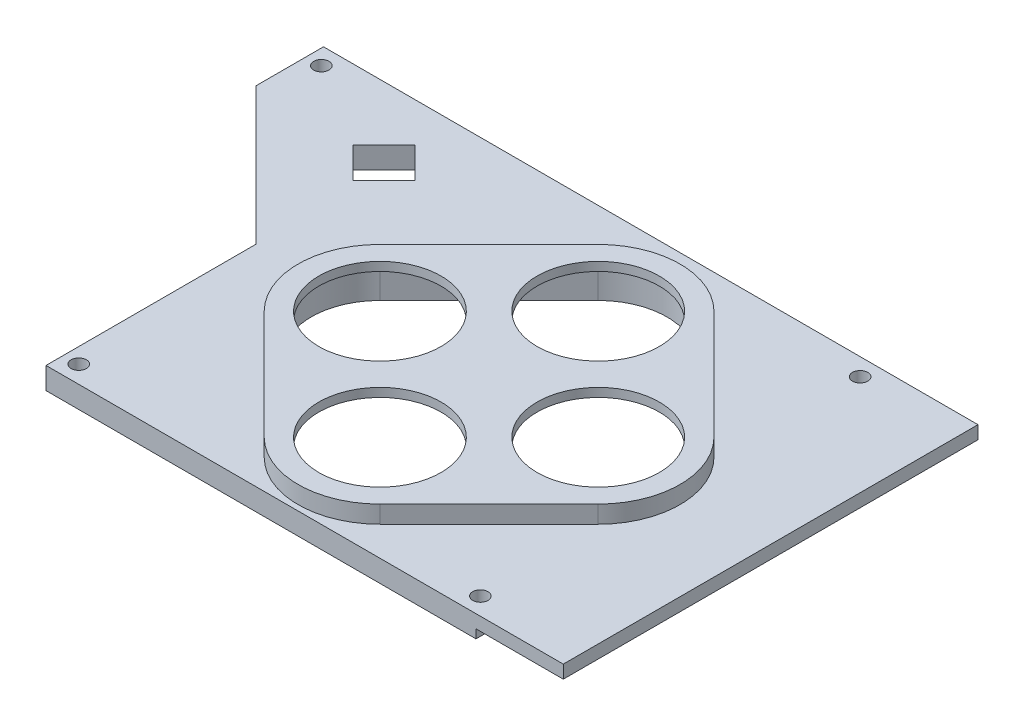
SolidWorks part; units mm, degrees
ref_plane "Front Plane" through (0, 0, 0) normal (0, 0, 1) x (1, 0, 0)
ref_plane "Top Plane" through (0, 0, 0) normal (0, 1, 0) x (1, 0, 0)
ref_plane "Right Plane" through (0, 0, 0) normal (1, 0, 0) x (0, 0, -1)
sketch "Sketch1" plane through (0, 0, 0) normal (0, 1, 0) x (1, 0, 0)
  line L1 (-100, 47.5) -> (100, 47.5)
  line L2 (-100, 47.5) -> (-100, -47.5)
  line L3 (-100, -47.5) -> (100, -47.5)
  line L4 (100, 47.5) -> (100, -47.5)
  line L5 (-100, 47.5) -> (100, -47.5) construction
  line L6 (-100, -47.5) -> (100, 47.5) construction
  circle A0 centre (-96, 43.5) radius 1.75
  circle A1 centre (-96, -43.5) radius 1.75
  circle A2 centre (97, 43.5) radius 1.75
  circle A3 centre (97, -43.5) radius 1.75
  point P0 (0, 0)
  dimension "D4" = 3.5
  dimension "D1" = 200
  dimension "D2" = 95
  dimension "D3" = 4
  dimension "D5" = 4
  dimension "D6" = 4
  dimension "D7" = 4
  dimension "D8" = 3
  dimension "D9" = 4
  dimension "D10" = 4
  dimension "D11" = 3
extrude "Boss-Extrude1" add sketch "Sketch1" along normal blind 5
sketch "Sketch2" plane through (0, 5, 0) normal (0, 1, 0) x (1, 0, 0)
  line L0 (-100, 47.5) -> (-100, -47.5) construction
  line L1 (-100, -47.5) -> (100, -47.5) construction
  line L3 (100, -47.5) -> (100, 47.5) construction
  line L4 (58, 22.5) -> (58, -27.5) construction
  line L5 (33, -2.5) -> (83, -2.5) construction
  line L6 (21.8631, -13.6369) -> (46.8631, -38.6369)
  line L7 (69.1369, -38.6369) -> (94.1369, -13.6369)
  line L8 (46.8631, 33.6369) -> (21.8631, 8.6369)
  line L9 (69.1369, 33.6369) -> (94.1369, 8.6369)
  circle A0 centre (-82, -27.5) radius 12.5
  circle A1 centre (58, 22.5) radius 15.75
  circle A2 centre (58, -27.5) radius 15.75
  circle A3 centre (83, -2.5) radius 15.75
  circle A4 centre (33, -2.5) radius 15.75
  point P13 (58, -2.5)
  point P17 (58, -2.5)
  dimension "D3" = 25
  dimension "D4" = 31.5
  dimension "D1" = 18
  dimension "D2" = 20
  dimension "D5" = 42
  dimension "D6" = 20
  dimension "D7" = 50
extrude "Cut-Extrude1" cut sketch "Sketch2" against normal up to surface (5 mm away) contours A4 | A4 L6 A2 L7 A3 L9 A1 L8 | A2 | A3 | A1 | A0 up to face at (0, 0, 0)
sketch "Sketch4" plane through (0, 0, 0) normal (0, -1, 0) x (1, 0, 0)
  line L0 (-100, -47.5) -> (-100, 47.5) construction
  line L1 (-93.5, 41) -> (-71.5, 41)
  line L2 (-93.5, 41) -> (-93.5, -41)
  line L3 (-93.5, -41) -> (-71.5, -41)
  line L4 (-71.5, 41) -> (-71.5, -41)
  line L5 (-93.5, 41) -> (-71.5, -41) construction
  line L6 (-93.5, -41) -> (-71.5, 41) construction
  line L7 (-100, 0) -> (-82.5, 0) construction
  line L8 (-82.5, 0) -> (-82.5, -19.5) construction
  line L9 (-90.5, -1) -> (-74.5, -1)
  line L10 (-90.5, -1) -> (-90.5, -38)
  line L11 (-90.5, -38) -> (-74.5, -38)
  line L12 (-74.5, -1) -> (-74.5, -38)
  line L13 (-90.5, -1) -> (-74.5, -38) construction
  line L14 (-90.5, -38) -> (-74.5, -1) construction
  point P0 (-82.5, 0)
  point P11 (-82.5, -19.5)
  circle M17 centre (-82, 27.5) radius 12.5
  dimension "D1" = 22
  dimension "D2" = 6.5
  dimension "D3" = 82
  dimension "D4" = 3
  dimension "D5" = 3
  dimension "D6" = 40
extrude "Boss-Extrude2" add sketch "Sketch4" along normal blind 4.2 contours L4 L2 L3 L9 L12 L11 L10 M17
sketch "Sketch5" plane through (0, 5, 0) normal (0, 1, 0) x (1, 0, 0)
  circle A0 centre (-82, -27.5) radius 17
  dimension "D1" = 34
sketch "Sketch6" plane through (0, 5, 0) normal (0, 1, 0) x (1, 0, 0)
  line L0 (-100, -47.5) -> (100, -47.5) construction
  line L1 (-100, 47.5) -> (-120, 47.5)
  line L2 (-100, 47.5) -> (-100, -47.5)
  line L3 (-100, -47.5) -> (-120, -47.5)
  line L4 (-120, 47.5) -> (-120, -47.5)
  line L5 (100, 47.5) -> (120, 47.5)
  line L6 (100, 47.5) -> (100, -47.5)
  line L7 (100, -47.5) -> (120, -47.5)
  line L8 (120, 47.5) -> (120, -47.5)
  dimension "D1" = 20
extrude "Boss-Extrude3" add sketch "Sketch6" against normal blind 3
sketch "Sketch8" plane through (0, 5, 0) normal (0, 1, 0) x (1, 0, 0)
  line L20 (71.2583, -40.7583) -> (96.2583, -15.7583)
  line L21 (19.7417, -15.7583) -> (44.7417, -40.7583)
  line L22 (44.7417, 35.7583) -> (19.7417, 10.7583)
  line L23 (96.2583, 10.7583) -> (71.2583, 35.7583)
  line L24 (71.2583, -40.7583) -> (96.2583, -15.7583)
  line L25 (19.7417, -15.7583) -> (44.7417, -40.7583)
  line L26 (44.7417, 35.7583) -> (19.7417, 10.7583)
  line L27 (96.2583, 10.7583) -> (71.2583, 35.7583)
  line L48 (21.8631, -13.6369) -> (46.8631, -38.6369)
  line L49 (69.1369, -38.6369) -> (94.1369, -13.6369)
  line L50 (94.1369, 8.6369) -> (69.1369, 33.6369)
  line L51 (46.8631, 33.6369) -> (21.8631, 8.6369)
  line L52 (21.8631, -13.6369) -> (46.8631, -38.6369)
  line L53 (69.1369, -38.6369) -> (94.1369, -13.6369)
  line L54 (94.1369, 8.6369) -> (69.1369, 33.6369)
  line L55 (46.8631, 33.6369) -> (21.8631, 8.6369)
  arc A8 (96.2583, -15.7583) -> (96.2583, 10.7583) centre (83, -2.5) ccw
  arc A9 (44.7417, -40.7583) -> (71.2583, -40.7583) centre (58, -27.5) ccw
  arc A10 (19.7417, 10.7583) -> (19.7417, -15.7583) centre (33, -2.5) ccw
  arc A11 (71.2583, 35.7583) -> (44.7417, 35.7583) centre (58, 22.5) ccw
  arc A12 (96.2583, -15.7583) -> (96.2583, 10.7583) centre (83, -2.5) ccw
  arc A13 (44.7417, -40.7583) -> (71.2583, -40.7583) centre (58, -27.5) ccw
  arc A14 (19.7417, 10.7583) -> (19.7417, -15.7583) centre (33, -2.5) ccw
  arc A15 (71.2583, 35.7583) -> (44.7417, 35.7583) centre (58, 22.5) ccw
  arc A32 (21.8631, 8.6369) -> (21.8631, -13.6369) centre (33, -2.5) ccw
  arc A33 (46.8631, -38.6369) -> (69.1369, -38.6369) centre (58, -27.5) ccw
  arc A34 (94.1369, -13.6369) -> (94.1369, 8.6369) centre (83, -2.5) ccw
  arc A35 (69.1369, 33.6369) -> (46.8631, 33.6369) centre (58, 22.5) ccw
  arc A36 (21.8631, 8.6369) -> (21.8631, -13.6369) centre (33, -2.5) ccw
  arc A37 (46.8631, -38.6369) -> (69.1369, -38.6369) centre (58, -27.5) ccw
  arc A38 (94.1369, -13.6369) -> (94.1369, 8.6369) centre (83, -2.5) ccw
  arc A39 (69.1369, 33.6369) -> (46.8631, 33.6369) centre (58, 22.5) ccw
  dimension "D1" = 3
  dimension "D2" = 0
extrude "Boss-Extrude4" add sketch "Sketch8" along normal blind 4
sketch "Sketch9" plane through (0, 9, 0) normal (0, 1, 0) x (1, 0, 0)
  line L24 (21.8631, -13.6369) -> (46.8631, -38.6369)
  line L25 (69.1369, -38.6369) -> (94.1369, -13.6369)
  line L26 (94.1369, 8.6369) -> (69.1369, 33.6369)
  line L27 (46.8631, 33.6369) -> (21.8631, 8.6369)
  line L28 (21.8631, -13.6369) -> (46.8631, -38.6369)
  line L29 (69.1369, -38.6369) -> (94.1369, -13.6369)
  line L30 (94.1369, 8.6369) -> (69.1369, 33.6369)
  line L31 (46.8631, 33.6369) -> (21.8631, 8.6369)
  circle A0 centre (58, 22.5) radius 14
  circle A1 centre (83, -2.5) radius 14
  circle A2 centre (58, -27.5) radius 14
  circle A3 centre (33, -2.5) radius 14
  arc A24 (21.8631, 8.6369) -> (21.8631, -13.6369) centre (33, -2.5) ccw
  arc A25 (46.8631, -38.6369) -> (69.1369, -38.6369) centre (58, -27.5) ccw
  arc A26 (94.1369, -13.6369) -> (94.1369, 8.6369) centre (83, -2.5) ccw
  arc A27 (69.1369, 33.6369) -> (46.8631, 33.6369) centre (58, 22.5) ccw
  arc A28 (21.8631, 8.6369) -> (21.8631, -13.6369) centre (33, -2.5) ccw
  arc A29 (46.8631, -38.6369) -> (69.1369, -38.6369) centre (58, -27.5) ccw
  arc A30 (94.1369, -13.6369) -> (94.1369, 8.6369) centre (83, -2.5) ccw
  arc A31 (69.1369, 33.6369) -> (46.8631, 33.6369) centre (58, 22.5) ccw
  dimension "D1" = 28
  dimension "D2" = 0
extrude "Boss-Extrude5" add sketch "Sketch9" against normal blind 2
sketch "Sketch10" plane through (0, 5, 0) normal (0, 1, 0) x (1, 0, 0)
  line L0 (0, 47.5) -> (0, 38.5) construction
  line L1 (120, 47.5) -> (-120, 47.5) construction
  line L2 (0, 38.5) -> (-7.0711, 31.4289)
  line L3 (-7.0711, 31.4289) -> (0, 24.3579)
  line L4 (0, 24.3579) -> (7.0711, 31.4289)
  line L5 (0, 38.5) -> (7.0711, 31.4289)
  line L6 (0, 38.5) -> (0, 24.3579) construction
  dimension "D1" = 9
  dimension "D2" = 10
extrude "Cut-Extrude2" cut sketch "Sketch10" against normal up to surface (5 mm away) up to face at (97, 0, 45.25)
sketch "Sketch11" plane through (0, 5, 0) normal (0, 1, 0) x (1, 0, 0)
  line L0 (-7.0711, 31.4289) -> (-31.4289, 31.4289) construction
  line L1 (0, 24.3579) -> (0, 0) construction
  line L2 (-31.4289, 31.4289) -> (0, 0)
  line L3 (0, 0) -> (0, -47.5)
  line L4 (-120, -47.5) -> (120, -47.5) construction
  line L5 (-31.4289, 31.4289) -> (-31.4289, 47.5)
  line L6 (120, 47.5) -> (-120, 47.5) construction
  line L7 (-120, 0) -> (0, 0) construction
  line L8 (-120, 47.5) -> (-120, -47.5) construction
  line L9 (-36.4289, 43.5) -> (-26.4289, 43.5) construction
  line L10 (-120, 47.5) -> (120, 47.5)
  line L11 (-120, 47.5) -> (-120, -47.5)
  line L12 (-120, -47.5) -> (120, -47.5)
  line L13 (120, 47.5) -> (120, -47.5)
  line L14 (-5, -43.5) -> (5, -43.5) construction
  circle A0 centre (-5, -43.5) radius 1.75
  circle A1 centre (5, -43.5) radius 1.75
  circle A2 centre (-26.4289, 43.5) radius 1.75
  circle A3 centre (-36.4289, 43.5) radius 1.75
  point P34 (-31.4289, 43.5)
  point P37 (0, -43.5)
  dimension "D2" = 3.5
  dimension "D1" = 10
  dimension "D3" = 4
  dimension "D4" = 4
extrude "Cut-Extrude3" cut sketch "Sketch11" along direction (0, 1, 0) on the side against the normal blind 10 contours A3 | A2 | A1 | A0
sketch "Sketch14" plane through (0, 5, 0) normal (0, 1, 0) x (1, 0, 0)
  line L0 (-7.0711, 31.4289) -> (-31.4289, 31.4289) construction
  line L1 (0, 24.3579) -> (0, 0) construction
  line L2 (-31.4289, 31.4289) -> (0, 0)
  line L3 (0, 0) -> (0, -47.5)
  line L4 (-120, -47.5) -> (120, -47.5) construction
  line L5 (-31.4289, 31.4289) -> (-31.4289, 47.5)
  line L6 (120, 47.5) -> (-120, 47.5) construction
  line L7 (-120, 0) -> (0, 0) construction
  line L8 (-120, 47.5) -> (-120, -47.5) construction
  line L10 (-120, 47.5) -> (120, 47.5)
  line L11 (-120, 47.5) -> (-120, -47.5)
  line L12 (-120, -47.5) -> (120, -47.5)
  line L13 (120, 47.5) -> (120, -47.5)
  circle M3 centre (-36.4289, 43.5) radius 1.75
  circle M4 centre (-5, -43.5) radius 1.75
  circle M12 centre (-96, -43.5) radius 1.75
  line M13 (-120, -47.5) -> (120, -47.5)
  line M15 (120, 47.5) -> (-120, 47.5)
  line M16 (-120, 47.5) -> (-120, -47.5)
  circle M17 centre (-96, 43.5) radius 1.75
  circle M19 centre (-82, -27.5) radius 12.5
extrude "Cut-Extrude4" cut sketch "Sketch14" against normal blind 10 contours L2 L5 L3 M15 M16 M13 M3 M19 M17 M12 M4 | M19
sketch "Sketch15" plane through (0, 5, 0) normal (0, 1, 0) x (1, 0, 0)
  line L6 (-29.9289, 47.5) -> (-31.4289, 47.5)
  line L7 (-31.4289, 47.5) -> (-31.4289, 31.4289)
  line L8 (-31.4289, 31.4289) -> (0, 0)
  line L9 (1.5, -47.5) -> (1.5, 0.6213)
  line L10 (1.5, 0.6213) -> (-29.9289, 32.0503)
  line L11 (-29.9289, 32.0503) -> (-29.9289, 47.5)
  line L12 (1.5, -47.5) -> (1.5, 0.6213)
  line L13 (1.5, 0.6213) -> (-29.9289, 32.0503)
  line L14 (-29.9289, 32.0503) -> (-29.9289, 47.5)
  line L15 (0, 0) -> (0, -47.5)
  line L16 (0, -47.5) -> (1.5, -47.5)
  dimension "D1" = 1.5
extrude "Cut-Extrude5" cut sketch "Sketch15" against normal up to surface (5 mm away) up to face at (58, 0, 2.5)
equation "\"D1@Boss-Extrude4\"=13-5-4"
